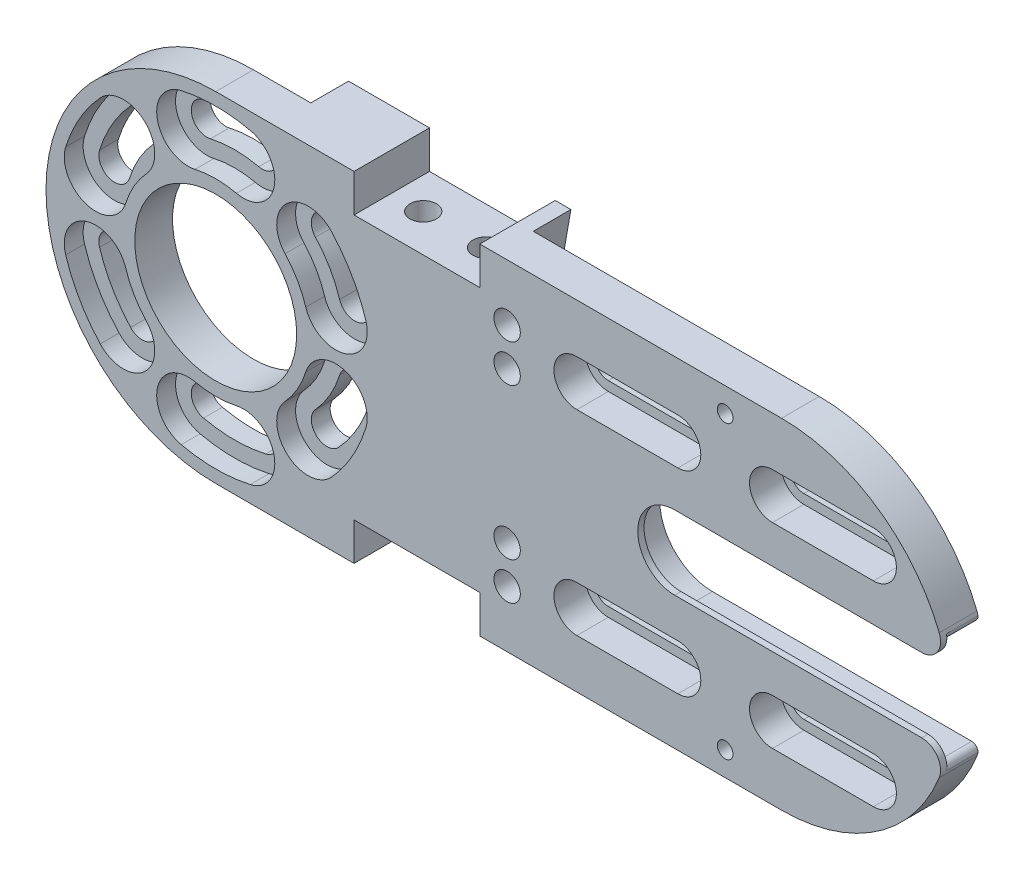
SolidWorks part; units mm, degrees
ref_plane "Front Plane" through (0, 0, 0) normal (0, 0, 1) x (1, 0, 0)
ref_plane "Top Plane" through (0, 0, 0) normal (0, 1, 0) x (1, 0, 0)
ref_plane "Right Plane" through (0, 0, 0) normal (1, 0, 0) x (0, 0, -1)
sketch "Sketch1" plane through (0, 0, 0) normal (0, 0, 1) x (1, 0, 0)
  line L0 (45, 0) -> (-45, 0) construction
  line L1 (45, -27) -> (-45, -27)
  line L2 (45, 27) -> (-45, 27)
  arc A1 (45, -27) -> (45, 27) centre (45, 0) ccw
  arc A2 (-45, 27) -> (-45, -27) centre (-45, 0) ccw
  point P3 (0, 0)
  dimension "D1" = 54
  dimension "D2" = 144
extrude "Boss-Extrude1" add sketch "Sketch1" along normal blind 6
sketch "Sketch2" plane through (0, 0, 6) normal (0, 0, 1) x (1, 0, 0)
  circle A0 centre (-45, 0) radius 12.875
  dimension "D1" = 25.75
extrude "Cut-Extrude1" cut sketch "Sketch2" against normal through all
sketch "Sketch3" plane through (0, 0, 6) normal (0, 0, 1) x (1, 0, 0)
  line L0 (-49.3944, 19.5113) -> (-45, 0) construction
  line L1 (-45, 0) -> (-40.6056, 19.5113) construction
  line L2 (-45, 20) -> (-45, 0) construction
  line L3 (-62.3205, 10) -> (-45, 0) construction
  arc A0 (-40.6056, 19.5113) -> (-49.3944, 19.5113) centre (-45, 0) ccw construction
  arc A1 (-39.507, 24.3891) -> (-50.493, 24.3891) centre (-45, 0) ccw
  arc A2 (-41.7042, 14.6335) -> (-48.2958, 14.6335) centre (-45, 0) ccw
  arc A3 (-41.7042, 14.6335) -> (-39.507, 24.3891) centre (-40.6056, 19.5113) ccw
  arc A4 (-50.493, 24.3891) -> (-48.2958, 14.6335) centre (-49.3944, 19.5113) ccw
  arc A6 (-64.0944, 5.95) -> (-59.7001, 13.5613) centre (-45, 0) cw construction
  arc A7 (-63.3751, 16.9516) -> (-68.868, 7.4375) centre (-45, 0) ccw construction
  arc A8 (-56.0251, 10.171) -> (-59.3208, 4.4625) centre (-45, 0) ccw construction
  arc A9 (-56.0251, 10.171) -> (-63.3751, 16.9516) centre (-59.7001, 13.5613) ccw construction
  arc A10 (-68.868, 7.4375) -> (-59.3208, 4.4625) centre (-64.0944, 5.95) ccw construction
  point P4 (-45, 20)
  point P16 (-62.3205, 10)
  dimension "D3" = 60
  dimension "D4" = 1.9
  dimension "D5" = 5
  dimension "D6" = 20
extrude "Cut-Extrude2" cut sketch "Sketch3" against normal blind 3
sketch "Sketch4" plane through (0, 0, 6) normal (0, 0, 1) x (1, 0, 0)
  arc A0 (-49.3944, 19.5113) -> (-40.6056, 19.5113) centre (-45, 0) cw construction
  arc A1 (-40.0563, 21.9502) -> (-49.9437, 21.9502) centre (-45, 0) ccw
  arc A2 (-41.1549, 17.0724) -> (-48.8451, 17.0724) centre (-45, 0) ccw
  arc A3 (-41.1549, 17.0724) -> (-40.0563, 21.9502) centre (-40.6056, 19.5113) ccw
  arc A4 (-49.9437, 21.9502) -> (-48.8451, 17.0724) centre (-49.3944, 19.5113) ccw
  arc A5 (-40.6056, 19.5113) -> (-49.3944, 19.5113) centre (-45, 0) ccw construction
  point P3 (-45, 20)
  point P10 (-48, 20.903)
  dimension "D1" = 2.5
extrude "Cut-Extrude3" cut sketch "Sketch4" against normal through all
pattern_circular "CirPattern1" count 6 over 360 about axis through (-45, 0, 0) along (0, 0, 1) of "Cut-Extrude2", "Cut-Extrude3"
sketch "Sketch5" plane through (0, 0, 0) normal (0, 0, -1) x (-1, 0, 0)
  line L0 (-72, 0) -> (-28, 0) construction
  line L1 (-72, 8.375) -> (-28, 8.375)
  line L2 (-72, -8.375) -> (-28, -8.375)
  arc A0 (-72, 8.375) -> (-72, -8.375) centre (-72, 0) ccw
  arc A1 (-28, -8.375) -> (-28, 8.375) centre (-28, 0) ccw
  arc A2 (-45, 27) -> (-45, -27) centre (-45, 0) ccw construction
  circle A3 centre (45, 0) radius 12.875 construction
  point P3 (-50, 0)
  point P8 (-76.5146, 8.375)
  point P9 (-75, 0)
  dimension "D2" = 51.75
  dimension "D1" = 16.75
extrude "Cut-Extrude4" cut sketch "Sketch5" against normal blind 5
fillet "Fillet1" radius 1 2 edges at (70.6683, -8.375, 2.5) (70.6683, 8.375, 2.5)
sketch "Sketch6" plane through (0, 0, 0) normal (0, 0, -1) x (-1, 0, 0)
  line L0 (-72, 0) -> (-28, 0) construction
  line L1 (-72, 5.875) -> (-28, 5.875)
  line L2 (-72, -5.875) -> (-28, -5.875)
  arc A0 (-72, 5.875) -> (-72, -5.875) centre (-72, 0) ccw
  arc A1 (-28, -5.875) -> (-28, 5.875) centre (-28, 0) ccw
  point P4 (-50, 0)
  dimension "D1" = 11.75
extrude "Cut-Extrude5" cut sketch "Sketch6" against normal through all
fillet "Fillet2" radius 3 2 edges at (71.3531, -5.875, 5.5) (71.3531, 5.875, 5.5)
sketch "Sketch7" plane through (0, 0, 6) normal (0, 0, 1) x (1, 0, 0)
  line L0 (28.5063, 15.5563) -> (12.4437, 15.5563) construction
  line L1 (28.5063, 11.9063) -> (12.4437, 11.9063)
  line L2 (28.5063, 19.2063) -> (12.4437, 19.2063)
  line L3 (0, 0) -> (50, 0) construction
  line L4 (72, 0) -> (28, 0) construction
  line L5 (59.619, 15.5563) -> (43.5563, 15.5563) construction
  line L6 (59.619, 11.9063) -> (43.5563, 11.9063)
  line L7 (59.619, 19.2063) -> (43.5563, 19.2063)
  line L8 (28, 0) -> (12.4437, 15.5563) construction
  line L9 (28, 0) -> (43.5563, 15.5563) construction
  arc A0 (28.5063, 11.9063) -> (28.5063, 19.2063) centre (28.5063, 15.5563) ccw
  arc A1 (12.4437, 19.2063) -> (12.4437, 11.9063) centre (12.4437, 15.5563) ccw
  arc A2 (59.619, 11.9063) -> (59.619, 19.2063) centre (59.619, 15.5563) ccw
  arc A3 (43.5563, 19.2063) -> (43.5563, 11.9063) centre (43.5563, 15.5563) ccw
  point P2 (20.475, 15.5563)
  point P14 (51.5877, 15.5563)
  point P22 (29.9455, 15.4)
  point P24 (41.6403, 15.4)
  dimension "D3" = 7.75
  dimension "D2" = 7.3
  dimension "D4" = 22
extrude "Cut-Extrude6" cut sketch "Sketch7" against normal blind 5
sketch "Sketch8" plane through (0, 0, 6) normal (0, 0, 1) x (1, 0, 0)
  line L0 (12.4437, 15.5563) -> (28.5063, 15.5563) construction
  line L1 (12.4437, 17.7063) -> (28.5063, 17.7063)
  line L2 (12.4437, 13.4063) -> (28.5063, 13.4063)
  line L3 (43.5563, 15.5563) -> (59.619, 15.5563) construction
  line L4 (43.5563, 17.7063) -> (59.619, 17.7063)
  line L5 (43.5563, 13.4063) -> (59.619, 13.4063)
  arc A0 (12.4437, 17.7063) -> (12.4437, 13.4063) centre (12.4437, 15.5563) ccw
  arc A1 (28.5063, 13.4063) -> (28.5063, 17.7063) centre (28.5063, 15.5563) ccw
  arc A2 (43.5563, 17.7063) -> (43.5563, 13.4063) centre (43.5563, 15.5563) ccw
  arc A3 (59.619, 13.4063) -> (59.619, 17.7063) centre (59.619, 15.5563) ccw
  point P2 (20.475, 15.5563)
  point P10 (51.5877, 15.5563)
  dimension "D1" = 4.3
extrude "Cut-Extrude7" cut sketch "Sketch8" against normal through all
hole_wizard "M3x0.5 Tapped Hole1" positions "Sketch10" profile "Sketch11" tap size "M3x0.5" standard "ANSI Metric" end condition through all
sketch "Sketch10" plane through (0, 0, 6) normal (0, 0, 1) x (1, 0, 0)
  line L0 (28.5063, 15.5563) -> (36.0313, 23.15) construction
  line L1 (36.0313, 23.15) -> (43.5563, 15.5563) construction
  line L3 (45, 27) -> (-45, 27) construction
  point P0 (36.0313, 23.15)
  dimension "D1" = 3.85
sketch "Sketch11" plane through (36.0313, 23.15, 6) normal (1, 0, 0) x (0, -1, 0)
  line L0 (0, 0) -> (0, 6)
  line L1 (0, 6) -> (1.25, 6)
  line L2 (1.25, 6) -> (1.25, 0)
  line L5 (1.25, 0) -> (0, 0)
  line L11 (0, -6.35) -> (0, 107.95) construction
  dimension "Thru Tap Drill Dia." = 2.5
  dimension "Thru Tap Drill Depth" = 6
cosmetic thread "Hole Thread1" parameters "D2"=3
hole_wizard "M5x0.8 Tapped Hole1" positions "Sketch12" profile "Sketch13" tap size "M5x0.8" standard "ANSI Metric" end condition through all
sketch "Sketch12" plane through (0, 0, 6) normal (0, 0, 1) x (1, 0, 0)
  line L0 (45, 27) -> (-45, 27) construction
  line L2 (0, 0) -> (50, 0) construction
  arc A0 (12.4437, 19.2063) -> (12.4437, 11.9063) centre (12.4437, 15.5563) ccw construction
  point P0 (1.3497, 12)
  point P2 (1.3497, 18)
  dimension "D1" = 6
  dimension "D2" = 9
  dimension "D3" = 8
sketch "Sketch13" plane through (1.3497, 12, 6) normal (1, 0, 0) x (0, -1, 0)
  line L0 (0, 0) -> (0, 6)
  line L1 (0, 6) -> (2.1, 6)
  line L2 (2.1, 6) -> (2.1, 0)
  line L5 (2.1, 0) -> (0, 0)
  line L11 (0, -6.35) -> (0, 107.95) construction
  dimension "Thru Tap Drill Dia." = 4.2
  dimension "Thru Tap Drill Depth" = 6
cosmetic thread "Hole Thread4" parameters "D2"=5
cosmetic thread "Hole Thread5" parameters "D2"=5
sketch "Sketch14" plane through (0, 0, 0) normal (0, 0, -1) x (-1, 0, 0)
  line L0 (0.5, 27) -> (3.1669, 11.875)
  line L1 (-45, 27) -> (45, 27) construction
  line L2 (3.1669, 11.875) -> (19.0918, 11.875)
  line L3 (0.5, 27) -> (35.8759, 27)
  line L4 (0, 0) -> (19.0918, 0) construction
  arc A0 (19.0918, 11.875) -> (35.8759, 27) centre (45, 0) cw
  arc A2 (45, -27) -> (45, 27) centre (45, 0) ccw construction
  circle A3 centre (45, 0) radius 12.875 construction
  point P8 (0, 0)
  dimension "D2" = 1.5
  dimension "D1" = 23.75
  dimension "D3" = 44.5
  dimension "D4" = 100
extrude "Boss-Extrude2" add sketch "Sketch14" along normal blind 6
sketch "Sketch15" plane through (0, 0, 6) normal (0, 0, 1) x (1, 0, 0)
  line L0 (45, 27) -> (-45, 27) construction
  line L1 (-23, 27) -> (-3, 27)
  line L2 (-23, 27) -> (-23, 21)
  line L3 (-23, 21) -> (-3, 21)
  line L4 (-3, 27) -> (-3, 21)
  circle A0 centre (-45, 0) radius 12.875 construction
  point P6 (-3.5492, 21)
  dimension "D3" = 22
  dimension "D1" = 20
  dimension "D2" = 21
extrude "Cut-Extrude8" cut sketch "Sketch15" against normal through all
hole_wizard "M5x0.8 Tapped Hole2" positions "Sketch16" profile "Sketch17" tap size "M5x0.8" standard "ANSI Metric"
sketch "Sketch16" plane through (0, 21, 0) normal (0, 1, 0) x (1, 0, 0)
  line L1 (-13, 6) -> (-13, -6) construction
  line L2 (-23, 6) -> (-3, 6) construction
  line L3 (-23, -6) -> (-3, -6) construction
  point P0 (-18, 0)
  point P2 (-8, 0)
  dimension "D1" = 10
cosmetic thread "Hole Thread6" parameters "D1"=9.13, "D2"=5
cosmetic thread "Hole Thread7" parameters "D1"=9.13, "D2"=5
sketch "Sketch17" plane through (-18, 21, 0) normal (1, 0, 0) x (0, 0, 1)
  line L0 (0, 0) -> (0, 6.2618)
  line L1 (0, 6.2618) -> (2.1, 5)
  line L2 (2.1, 5) -> (2.1, 0)
  line L5 (2.1, 0) -> (0, 0)
  line L10 (0, 6.2618) -> (-2.1, 5) construction
  line L11 (0, -6.35) -> (0, 107.95) construction
  dimension "Tap Drill Dia." = 4.2
  dimension "Tap Drill Depth" = 5
  dimension "Drill Angle" = 118
mirror "Mirror1" about plane through (0, 0, 0) normal (0, 1, 0) of "Cut-Extrude8", "M5x0.8 Tapped Hole2", "Boss-Extrude2", "M5x0.8 Tapped Hole1", "M3x0.5 Tapped Hole1", "Cut-Extrude6", "Cut-Extrude7"
cosmetic thread "Hole Thread8" parameters "D1"=9.13, "D2"=5
cosmetic thread "Hole Thread9" parameters "D1"=9.13, "D2"=5
